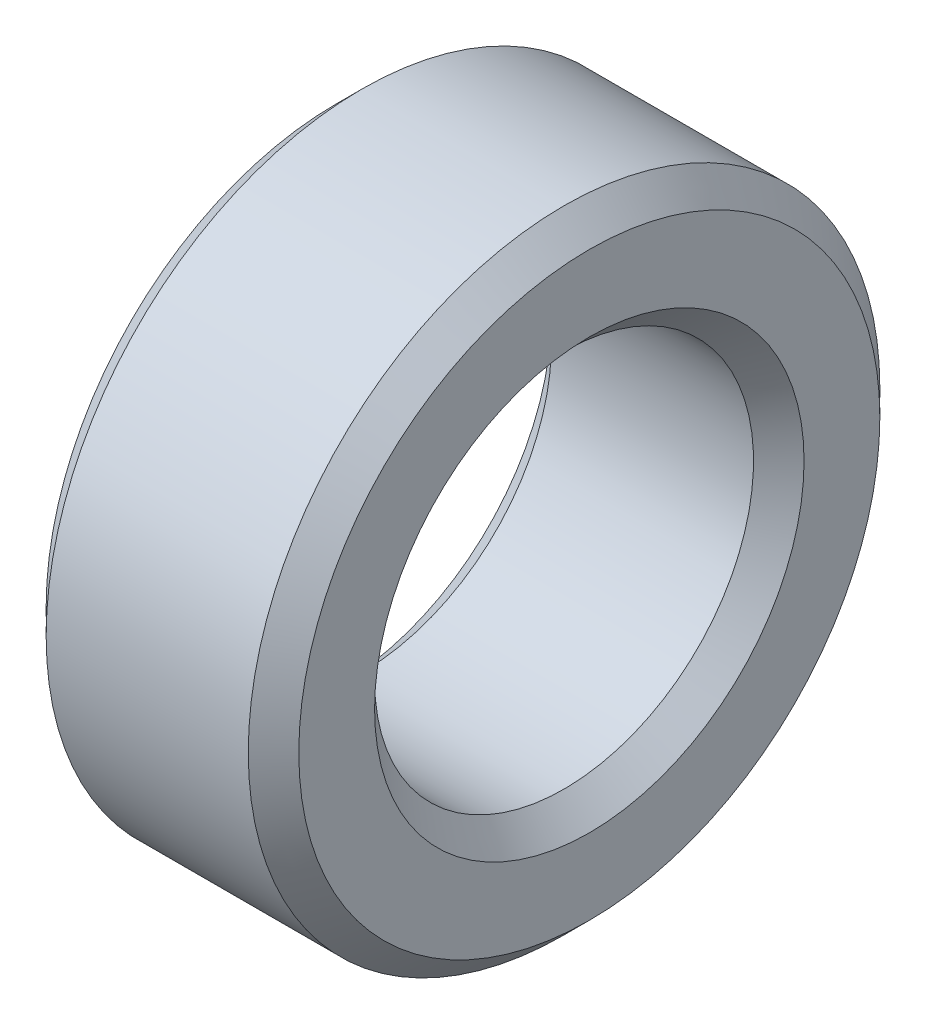
SolidWorks part; units mm, degrees
material "S45C相当"
ref_plane "Front Plane" through (0, 0, 0) normal (0, 0, 1) x (1, 0, 0)
ref_plane "Top Plane" through (0, 0, 0) normal (0, 1, 0) x (1, 0, 0)
ref_plane "Right Plane" through (0, 0, 0) normal (1, 0, 0) x (0, 0, -1)
sketch "Sketch1" plane through (0, 0, 0) normal (0, 0, 1) x (1, 0, 0)
  line L0 (0, 0) -> (2, 0) construction
  line L2 (0, 1.5) -> (2, 1.5)
  line L3 (0, 1.5) -> (0, 2.5)
  line L4 (0, 2.5) -> (2, 2.5)
  line L5 (2, 1.5) -> (2, 2.5)
  dimension "D" = 5
  dimension "V" = 3
  dimension "T" = 2
revolve "Revolve1" add sketch "Sketch1" angle 360 about L0
chamfer "Chamfer1" distance 0.2 angle 45 4 edges at (0, 0, 2.5) (2, 0, 2.5) (2, 0, 1.5) (0, 0, 1.5)
